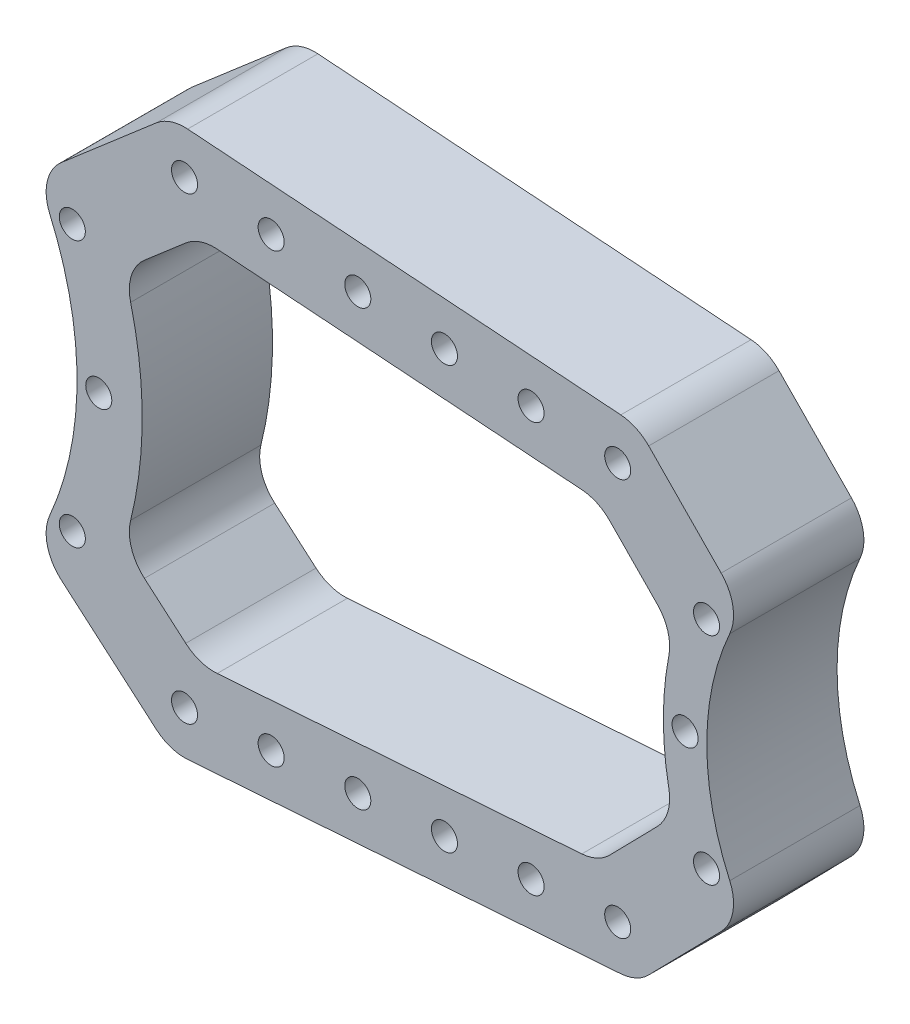
SolidWorks part; units mm, degrees
ref_plane "前视基准面" through (0, 0, 0) normal (0, 0, 1) x (1, 0, 0)
ref_plane "上视基准面" through (0, 0, 0) normal (0, 1, 0) x (1, 0, 0)
ref_plane "右视基准面" through (0, 0, 0) normal (1, 0, 0) x (0, 0, -1)
other "Configuration Table"
sketch "草图3" plane through (0, 0, 0) normal (0, 0, 1) x (1, 0, 0)
  line L0 (36.9552, -15.3073) -> (49.8729, -26.4376)
  line L1 (49.8729, -26.4376) -> (99.7459, -22.8753)
  line L2 (99.7459, -22.8753) -> (109.9739, -12.4372)
  line L3 (36.9552, 15.3073) -> (49.8729, 26.4376)
  line L4 (49.8729, 26.4376) -> (99.7459, 22.8753)
  line L5 (99.7459, 22.8753) -> (109.9739, 12.4372)
  line L6 (32.4388, -18.0159) -> (48.1718, -31.5719)
  line L7 (48.1718, -31.5719) -> (101.9915, -27.7276)
  line L8 (101.9915, -27.7276) -> (114.1851, -15.2836)
  line L9 (40.2189, -11.5195) -> (51.5741, -21.3034)
  line L10 (51.5741, -21.3034) -> (97.5003, -18.023)
  line L11 (97.5003, -18.023) -> (106.4026, -8.9378)
  line L12 (40.2189, 11.5195) -> (51.5741, 21.3034)
  line L13 (51.5741, 21.3034) -> (97.5003, 18.023)
  line L14 (97.5003, 18.023) -> (106.4026, 8.9378)
  line L15 (32.0167, 17.6522) -> (48.1718, 31.5719)
  line L16 (48.1718, 31.5719) -> (101.9915, 27.7276)
  line L17 (101.9915, 27.7276) -> (114.1732, 15.2957)
  line L18 (33.6914, -19.0952) -> (48.1718, -31.5719) construction
  line L19 (33.6914, 19.0952) -> (48.1718, 31.5719) construction
  line L20 (101.9915, -27.7276) -> (113.5452, -15.9366) construction
  line L21 (101.9915, 27.7276) -> (113.5452, 15.9366) construction
  line L22 (112.379, 17.1268) -> (115.1724, 14.276)
  circle A0 centre (140, 0) radius 32.5
  circle A1 centre (0, 0) radius 40
  circle A2 centre (140, 0) radius 35
  circle A4 centre (0, 0) radius 45
  circle A5 centre (0, 0) radius 37.5
  circle A6 centre (140, 0) radius 30
  dimension "D5" = 75
  dimension "D6" = 60
  dimension "D1" = 5
  dimension "D2" = 5
  dimension "D3" = 5
  dimension "D4" = 5
extrude "凸台-拉伸1" add sketch "草图3" along normal blind 15
fillet "圆角1" radius 5 1 edges at (101.9915, 27.7276, 7.5)
fillet "圆角2" radius 5 1 edges at (114.1851, 15.2836, 7.5)
fillet "圆角3" radius 5 1 edges at (114.1851, -15.2836, 7.5)
fillet "圆角4" radius 5 1 edges at (101.9915, -27.7276, 7.5)
fillet "圆角5" radius 5 1 edges at (48.1718, -31.5719, 7.5)
fillet "圆角6" radius 5 1 edges at (48.1718, 31.5719, 7.5)
fillet "圆角7" radius 5 1 edges at (32.7436, -18.2785, 7.5)
fillet "圆角8" radius 5 1 edges at (32.7436, 18.2785, 7.5)
fillet "圆角9" radius 5 1 edges at (97.5003, -18.023, 7.5)
fillet "圆角10" radius 5 1 edges at (106.2123, -9.132, 7.5)
fillet "圆角11" radius 5 1 edges at (106.2123, 9.132, 7.5)
fillet "圆角12" radius 5 1 edges at (97.5003, 18.023, 7.5)
fillet "圆角13" radius 5 1 edges at (51.5741, -21.3034, 7.5)
fillet "圆角14" radius 5 1 edges at (42.8391, -13.7771, 7.5)
fillet "圆角15" radius 5 1 edges at (42.8391, 13.7771, 7.5)
fillet "圆角16" radius 5 1 edges at (51.5741, 21.3034, 7.5)
sketch "草图5" plane through (0, 0, 0) normal (0, 0, -1) x (-1, 0, 0)
  circle A0 centre (-36.9552, 15.3073) radius 1.5
  circle A1 centre (-40, 0) radius 1.5
  circle A2 centre (-36.9552, -15.3073) radius 1.5
  circle A3 centre (-49.8729, -26.4376) radius 1.5
  circle A4 centre (-49.8729, 26.4376) radius 1.5
  circle A5 centre (-99.7459, 22.8753) radius 1.5
  circle A6 centre (-99.7459, -22.8753) radius 1.5
  circle A7 centre (-109.9739, 12.4372) radius 1.5
  circle A8 centre (-107.5, 0) radius 1.5
  circle A9 centre (-109.9739, -12.4372) radius 1.5
  circle A10 centre (-59.8475, 25.7252) radius 1.5
  circle A11 centre (-69.8221, 25.0127) radius 1.5
  circle A12 centre (-79.7967, 24.3002) radius 1.5
  circle A13 centre (-89.7713, 23.5878) radius 1.5
  circle A14 centre (-89.7713, -23.5878) radius 1.5
  circle A15 centre (-79.7967, -24.3002) radius 1.5
  circle A16 centre (-69.8221, -25.0127) radius 1.5
  circle A17 centre (-59.8475, -25.7252) radius 1.5
extrude "切除-拉伸1" cut sketch "草图5" against normal blind 15
